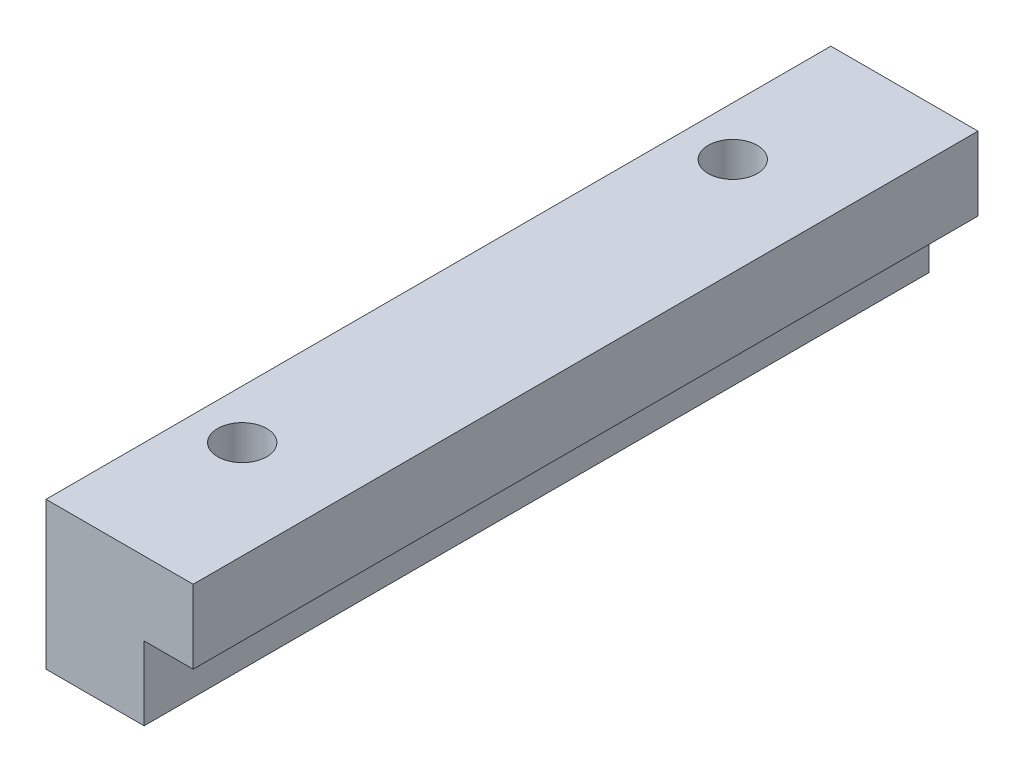
SolidWorks part; units mm, degrees
ref_plane "Front" through (0, 0, 0) normal (0, 0, 1) x (1, 0, 0)
ref_plane "Top" through (0, 0, 0) normal (0, 1, 0) x (1, 0, 0)
ref_plane "Right" through (0, 0, 0) normal (1, 0, 0) x (0, 0, -1)
sketch "Sketch1" plane through (0, 0, 0) normal (0, 1, 0) x (1, 0, 0)
  line L1 (-9.525, -50.8) -> (9.525, -50.8)
  line L2 (-9.525, -50.8) -> (-9.525, 50.8)
  line L3 (-9.525, 50.8) -> (9.525, 50.8)
  line L4 (9.525, -50.8) -> (9.525, 50.8)
  line L5 (-9.525, -50.8) -> (9.525, 50.8) construction
  line L6 (-9.525, 50.8) -> (9.525, -50.8) construction
  point P0 (0, 0)
  dimension "D1" = 101.6
  dimension "D2" = 19.05
extrude "Boss-Extrude1" add sketch "Sketch1" along normal mid plane 19.05 contours L4 L3 L2 L1
sketch "Sketch2" plane through (0, 0, 50.8) normal (0, 0, 1) x (1, 0, 0)
  line L0 (-9.525, 9.525) -> (9.525, 9.525) construction
  line L1 (3.175, 0) -> (9.525, 0)
  line L2 (3.175, 0) -> (3.175, -9.525)
  line L3 (3.175, -9.525) -> (9.525, -9.525)
  line L4 (9.525, 0) -> (9.525, -9.525)
  line L5 (3.175, 0) -> (9.525, -9.525) construction
  line L6 (3.175, -9.525) -> (9.525, 0) construction
  point P0 (6.35, -4.7625)
  dimension "D1" = 6.35
  dimension "D2" = 9.525
extrude "Cut-Extrude1" cut sketch "Sketch2" against normal through all
sketch "Sketch3" plane through (0, 9.525, 0) normal (0, 1, 0) x (1, 0, 0)
  line L0 (-3.175, 31.75) -> (-3.175, -31.75) construction
  line L1 (-50, 0) -> (50, 0) construction
  line L2 (-9.525, -50.8) -> (-9.525, 50.8) construction
  point P0 (-3.175, 31.75)
  point P1 (-3.175, -31.75)
  point P4 (-3.175, 0)
  dimension "D1" = 63.5
  dimension "D2" = 6.35
hole_wizard "1/4 (0.25) Diameter Hole1" positions "Sketch4" profile "Sketch6" hole size "1/4" standard "ANSI Inch"
sketch "Sketch4" plane through (0, 9.525, 0) normal (0, 1, 0) x (1, 0, 0)
  point P0 (-3.175, 31.75)
  point P3 (-3.175, -31.75)
sketch "Sketch6" plane through (-3.175, 9.525, -31.75) normal (1, 0, 0) x (0, 0, 1)
  line L0 (0, 0) -> (0, 27.3077)
  line L1 (0, 27.3077) -> (3.175, 25.4)
  line L2 (3.175, 25.4) -> (3.175, 0)
  line L5 (3.175, 0) -> (0, 0)
  line L10 (0, 27.3077) -> (-3.175, 25.4) construction
  line L11 (0, -6.35) -> (0, 107.95) construction
  dimension "Hole Dia." = 6.35
  dimension "Hole Depth" = 25.4
  dimension "Drill Angle" = 118
